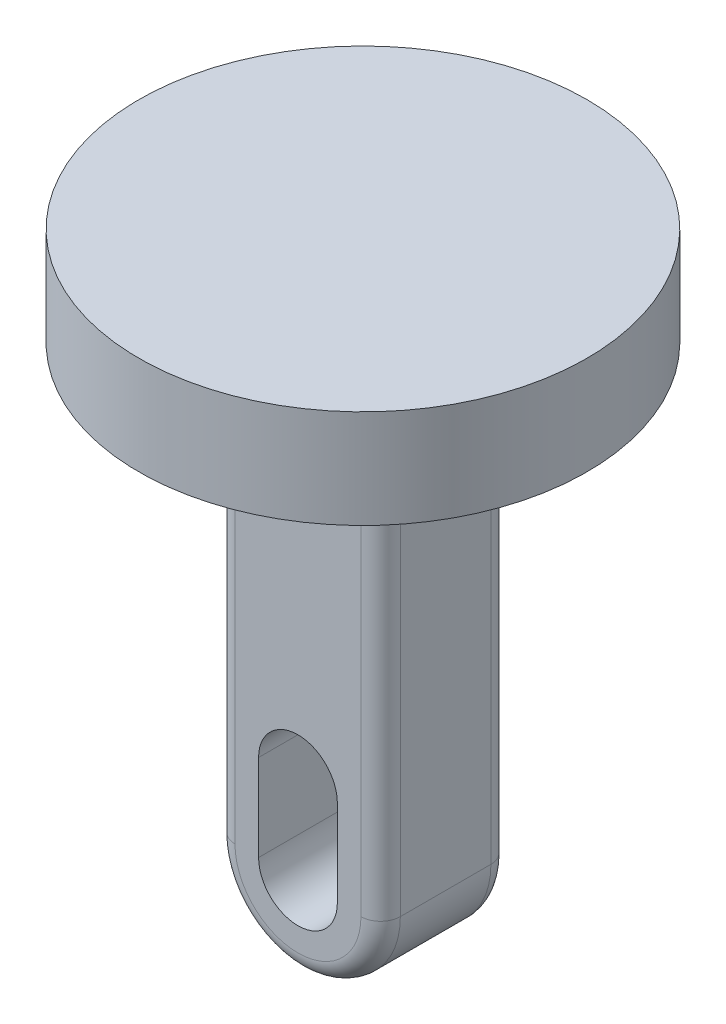
SolidWorks part; units mm, degrees
ref_plane "Front Plane" through (0, 0, 0) normal (0, 0, 1) x (1, 0, 0)
ref_plane "Top Plane" through (0, 0, 0) normal (0, 1, 0) x (1, 0, 0)
ref_plane "Right Plane" through (0, 0, 0) normal (1, 0, 0) x (0, 0, -1)
sketch "Sketch1" plane through (0, 0, 0) normal (0, 0, 1) x (1, 0, 0)
  line L0 (0, 0) -> (0, 77.2632) construction
  line L2 (2.1, 0) -> (2.1, 9.7)
  line L3 (2.1, 9.7) -> (-2.1, 9.7)
  line L4 (1, 0) -> (1, 2.2)
  line L5 (-1, 0) -> (-1, 2.2)
  line L6 (-2.1, 0) -> (-2.1, 9.7)
  arc A0 (-1, 0) -> (1, 0) centre (0, 0) ccw
  arc A1 (1, 2.2) -> (-1, 2.2) centre (0, 2.2) ccw
  arc A2 (-2.1, 0) -> (2.1, 0) centre (0, 0) ccw
  point P13 (0, 9.7)
  point P14 (0, 0)
  dimension "D1" = 2
  dimension "D2" = 2.2
  dimension "D3" = 4.2
  dimension "D4" = 9.7
extrude "Boss-Extrude1" add sketch "Sketch1" along normal mid plane 3.3
sketch "Sketch2" plane through (0, 0, 0) normal (0, 0, 1) x (1, 0, 0)
  line L0 (0, 9.7) -> (0, 40.6723) construction
  line L1 (2.1, 9.7) -> (-2.1, 9.7) construction
  line L2 (0, 13.5) -> (5.69, 13.5)
  line L3 (5.69, 13.5) -> (5.69, 11)
  line L4 (5.69, 11) -> (1.62, 11)
  line L5 (1.62, 11) -> (1.62, 9.7)
  line L6 (1.62, 9.7) -> (0, 9.7)
  line L7 (0, 9.7) -> (0, 13.5)
  dimension "D1" = 2.5
  dimension "D2" = 5.69
  dimension "D3" = 1.62
  dimension "D4" = 3.8
revolve "Revolve1" add sketch "Sketch2" angle 360 about L0
fillet "Fillet1" radius 0.5 6 edges at (0, -2.1, -1.65) (2.1, 4.85, -1.65) (-2.1, 4.85, -1.65) (2.1, 4.85, 1.65) (0, -2.1, 1.65) (-2.1, 4.85, 1.65)
sketch "Sketch3" plane through (0, 0, 0) normal (0, 0, 1) x (1, 0, 0)
  line L0 (0, 0) -> (0, 41.7776) construction
